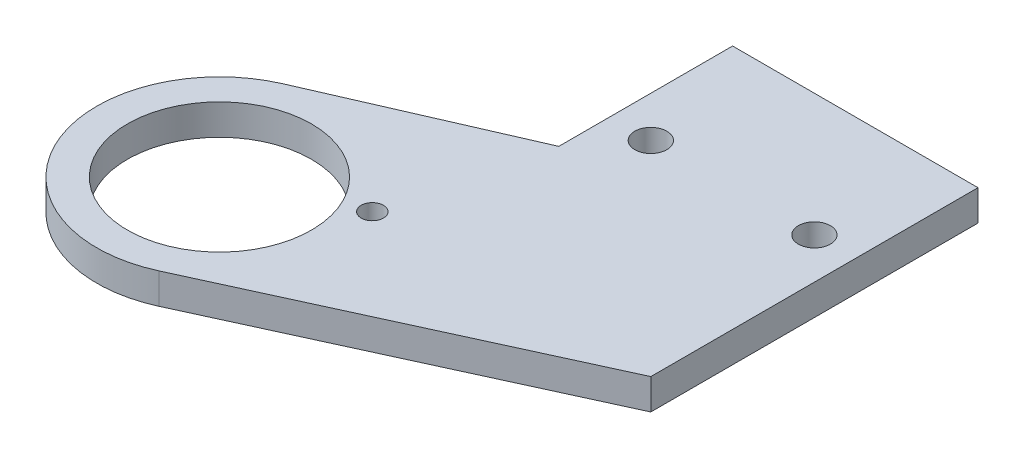
SolidWorks part; units mm, degrees
material "6061 Alloy"
ref_plane "Front Plane" through (0, 0, 0) normal (0, 0, 1) x (1, 0, 0)
ref_plane "Top Plane" through (0, 0, 0) normal (0, 1, 0) x (1, 0, 0)
ref_plane "Right Plane" through (0, 0, 0) normal (1, 0, 0) x (0, 0, -1)
sketch "Sketch2" plane through (0, 0, 0) normal (0, 1, 0) x (1, 0, 0)
  line L0 (19.05, 0) -> (-19.05, 0)
  line L1 (-19.05, 0) -> (-19.05, -26.9875)
  line L2 (-19.05, -26.9875) -> (-48.884, -39.9857)
  line L3 (19.05, 0) -> (19.05, -50.8)
  line L4 (-33.3415, -74.7695) -> (19.05, -50.8)
  circle A0 centre (-41.275, -57.4501) radius 14.2875
  arc A2 (-48.884, -39.9857) -> (-33.3415, -74.7695) centre (-41.275, -57.4501) ccw
extrude "Boss-Extrude1" add sketch "Sketch2" along normal blind 4.7625
sketch "Sketch3" plane through (0, 4.7625, 0) normal (0, 1, 0) x (1, 0, 0)
  line L0 (-41.275, -57.4501) -> (-24.742, -50.2469) construction
  line L1 (0, 0) -> (0, -19.05) construction
  line L2 (0, -19.05) -> (12.7, -19.05) construction
  line L3 (0, -19.05) -> (-12.7, -19.05) construction
  dimension "D1" = 25.4
hole_wizard "Tap Drill for #8-32 Tap1" positions "Sketch4" profile "Sketch5" hole size "#8-32" standard "ANSI Inch" end condition through all
sketch "Sketch4" plane through (0, 4.7625, 0) normal (0, 1, 0) x (1, 0, 0)
  point P0 (-24.742, -50.2469)
sketch "Sketch5" plane through (-24.742, 4.7625, 50.2469) normal (1, 0, 0) x (0, 0, 1)
  line L0 (0, 0) -> (0, 4.7625)
  line L1 (0, 4.7625) -> (1.7272, 4.7625)
  line L2 (1.7272, 4.7625) -> (1.7272, 0)
  line L5 (1.7272, 0) -> (0, 0)
  line L11 (0, -6.35) -> (0, 107.95) construction
  dimension "Thru Hole Dia." = 3.4544
  dimension "Thru Hole Depth" = 4.7625
hole_wizard "#10 Clearance Hole1" positions "Sketch6" profile "Sketch7" hole size "#10" standard "ANSI Inch" end condition through all
sketch "Sketch6" plane through (0, 4.7625, 0) normal (0, 1, 0) x (1, 0, 0)
  point P0 (-12.7, -19.05)
  point P3 (12.7, -19.05)
sketch "Sketch7" plane through (-12.7, 4.7625, 19.05) normal (1, 0, 0) x (0, 0, 1)
  line L0 (0, 0) -> (0, 4.7625)
  line L1 (0, 4.7625) -> (2.4892, 4.7625)
  line L2 (2.4892, 4.7625) -> (2.4892, 0)
  line L5 (2.4892, 0) -> (0, 0)
  line L11 (0, -6.35) -> (0, 107.95) construction
  dimension "Thru Hole Dia." = 4.9784
  dimension "Thru Hole Depth" = 4.7625
